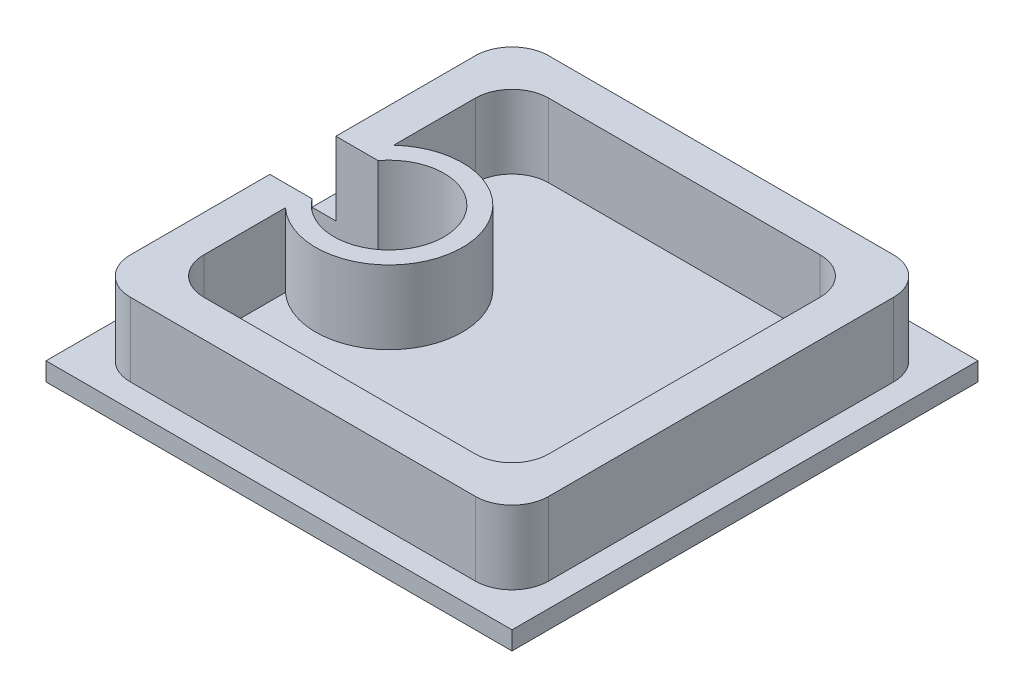
SolidWorks part; units mm, degrees
ref_plane "Front Plane" through (0, 0, 0) normal (0, 0, 1) x (1, 0, 0)
ref_plane "Top Plane" through (0, 0, 0) normal (0, 1, 0) x (1, 0, 0)
ref_plane "Right Plane" through (0, 0, 0) normal (1, 0, 0) x (0, 0, -1)
sketch "Sketch1" plane through (0, 0, 0) normal (0, 1, 0) x (1, 0, 0)
  line L1 (12.7, -12.7) -> (-12.7, -12.7)
  line L2 (12.7, -12.7) -> (12.7, 12.7)
  line L3 (12.7, 12.7) -> (-12.7, 12.7)
  line L4 (-12.7, -12.7) -> (-12.7, 12.7)
  line L5 (12.7, -12.7) -> (-12.7, 12.7) construction
  line L6 (12.7, 12.7) -> (-12.7, -12.7) construction
  point P0 (0, 0)
  dimension "D1" = 25.4
  dimension "D2" = 25.4
extrude "Boss-Extrude1" add sketch "Sketch1" along normal blind 1
sketch "Sketch2" plane through (0, 1, 0) normal (0, 1, 0) x (1, 0, 0)
  line L0 (-12.7, 12.7) -> (-12.7, -12.7) construction
  line L1 (-11.4, 11.4) -> (11.4, 11.4)
  line L2 (-11.4, 11.4) -> (-11.4, -11.4)
  line L3 (-11.4, -11.4) -> (11.4, -11.4)
  line L4 (11.4, 11.4) -> (11.4, -11.4)
  line L5 (-11.4, 11.4) -> (11.4, -11.4) construction
  line L6 (-11.4, -11.4) -> (11.4, 11.4) construction
  line L7 (12.7, 12.7) -> (-12.7, 12.7) construction
  line L8 (-9.4, 9.4) -> (-9.4, -9.4)
  line L9 (-9.4, -9.4) -> (9.4, -9.4)
  line L10 (9.4, 9.4) -> (9.4, -9.4)
  line L11 (-9.4, 9.4) -> (9.4, 9.4)
  point P0 (0, 0)
  dimension "D1" = 1.3
  dimension "D2" = 1.3
  dimension "D3" = 2
extrude "Boss-Extrude2" add sketch "Sketch2" along normal blind 4
fillet "Fillet1" radius 2 8 edges at (-9.4, 3, 9.4) (9.4, 3, 9.4) (9.4, 3, -9.4) (-9.4, 3, -9.4) (-11.4, 3, 11.4) (11.4, 3, 11.4) (11.4, 3, -11.4) (-11.4, 3, -11.4)
sketch "Sketch3" plane through (0, 5, 0) normal (0, 1, 0) x (1, 0, 0)
  line L0 (-12.7, 12.7) -> (-12.7, -12.7) construction
  line L1 (-6.7, 0) -> (-12.7, 0) construction
  line L3 (-12.7, 1.8) -> (-6.7, 1.8)
  line L4 (-12.7, 1.8) -> (-12.7, -1.8)
  line L5 (-12.7, -1.8) -> (-6.7, -1.8)
  line L6 (-6.7, 1.8) -> (-6.7, -1.8)
  line L7 (-12.7, 1.8) -> (-6.7, -1.8) construction
  line L8 (-12.7, -1.8) -> (-6.7, 1.8) construction
  circle A0 centre (-6.7, 0) radius 3
  point P5 (-9.7, 0)
  line M2 (-11.4, 9.4) -> (-11.4, -9.4)
  line M10 (-9.4, -7.4) -> (-9.4, 7.4)
  dimension "D1" = 6
  dimension "D2" = 6
  dimension "D3" = 3.6
extrude "Cut-Extrude1" cut sketch "Sketch3" against normal through all contours L3 A0 L5 L6 M10 | L4 L5 L3 M2 | A0 L3 L5 M10 M2 | L5 A0 L3 L6 | A0 L3 M10 | A0 M10 | A0 L5 M10
sketch "Sketch4" plane through (0, 1, 0) normal (0, 1, 0) x (1, 0, 0)
  line L9 (-9.1, 1.8) -> (-9.4, 1.8)
  line L10 (-9.4, 1.8) -> (-9.4, 2.9513)
  line L11 (-9.4, 7.4) -> (-9.4, 1.8) construction
  line L12 (-9.1, -1.8) -> (-9.4, -1.8)
  line L13 (-9.4, -1.8) -> (-9.4, -2.9513)
  arc A8 (-9.9, -2.4) -> (-9.9, 2.4) centre (-6.7, 0) ccw
  arc A9 (-9.4, -2.9513) -> (-9.4, 2.9513) centre (-6.7, 0) ccw
  arc A11 (-9.1, -1.8) -> (-9.1, 1.8) centre (-6.7, 0) ccw
  arc A12 (-9.1, -1.8) -> (-9.1, 1.8) centre (-6.7, 0) ccw
  dimension "D1" = 1
  dimension "D2" = 0
extrude "Boss-Extrude3" add sketch "Sketch4" along normal up to surface (4 mm away) up to face at (-2.08, 5, 0)
